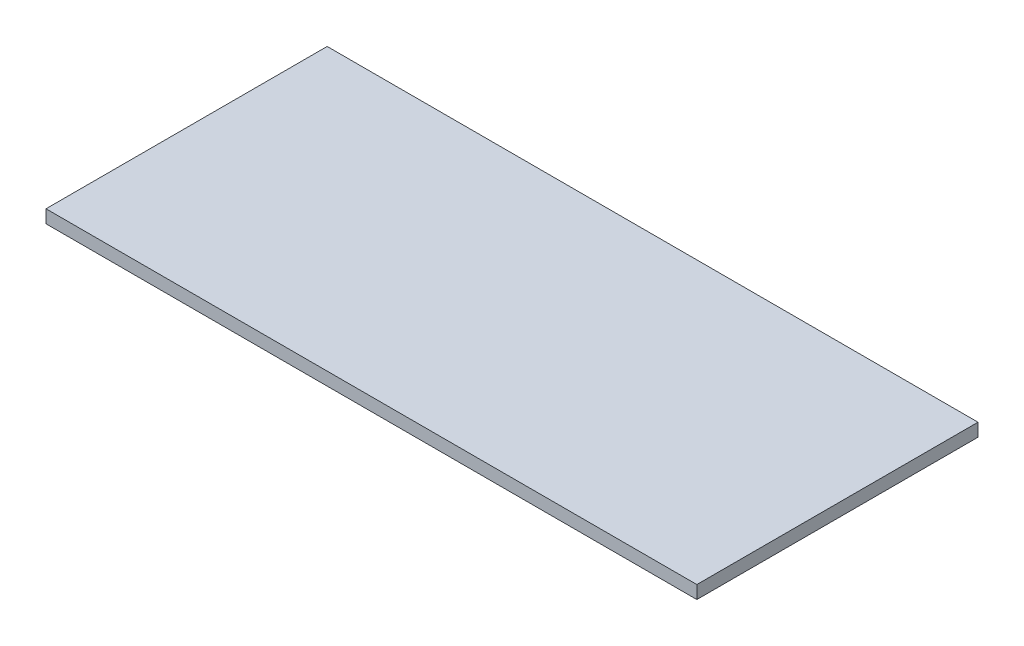
SolidWorks part; units mm, degrees
material "Mogano"
ref_plane "Piano frontale" through (0, 0, 0) normal (0, 0, 1) x (1, 0, 0)
ref_plane "Piano superiore" through (0, 0, 0) normal (0, 1, 0) x (1, 0, 0)
ref_plane "Piano destro" through (0, 0, 0) normal (1, 0, 0) x (0, 0, -1)
sketch "Schizzo1" plane through (0, 0, 0) normal (0, 1, 0) x (1, 0, 0)
  line L1 (-1250, 540) -> (1250, 540)
  line L2 (-1250, 540) -> (-1250, -540)
  line L3 (-1250, -540) -> (1250, -540)
  line L4 (1250, 540) -> (1250, -540)
  line L5 (-1250, 540) -> (1250, -540) construction
  line L6 (-1250, -540) -> (1250, 540) construction
  point P0 (0, 0)
  dimension "D1" = 1080
  dimension "D2" = 2500
extrude "Estrusione-Estrusione1" add sketch "Schizzo1" along normal blind 50
